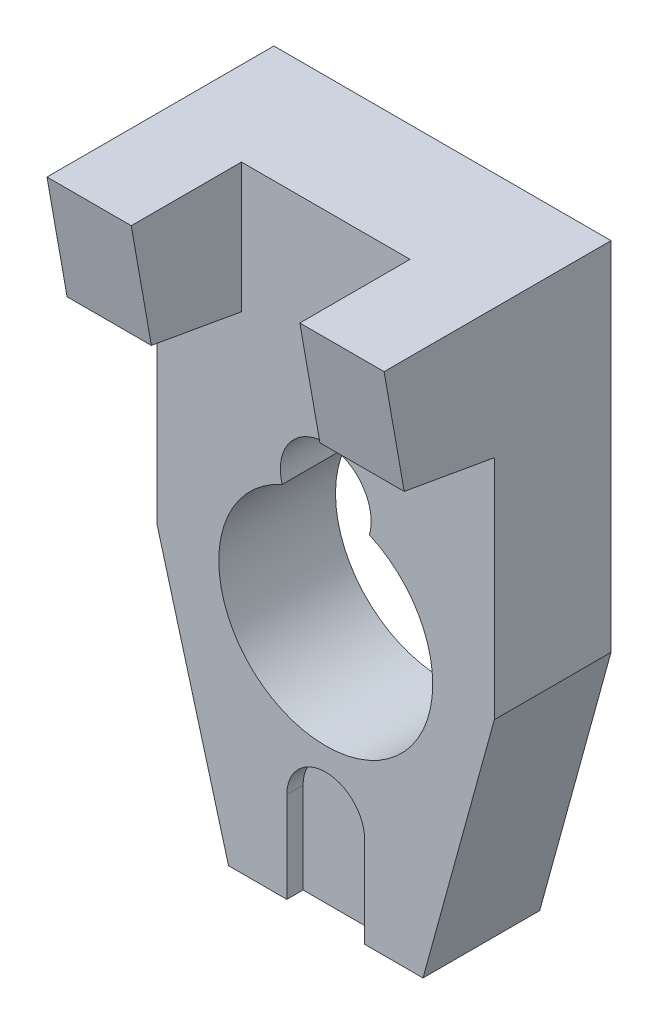
SolidWorks part; units mm, degrees
ref_plane "前视基准面" through (0, 0, 0) normal (0, 0, 1) x (1, 0, 0)
ref_plane "上视基准面" through (0, 0, 0) normal (0, 1, 0) x (1, 0, 0)
ref_plane "右视基准面" through (0, 0, 0) normal (1, 0, 0) x (0, 0, -1)
other "Configuration Table"
sketch "草图1" plane through (0, 0, 0) normal (0, 0, 1) x (1, 0, 0)
  line L0 (-26, 0) -> (-15, -40)
  line L1 (-26, 55) -> (26, 55)
  line L2 (-26, 55) -> (-26, 0)
  line L4 (26, 55) -> (26, 0)
  line L5 (-26, 55) -> (16.4377, -34.772) construction
  line L6 (-16.4377, -34.772) -> (26, 55) construction
  line L7 (-15, -40) -> (15, -40)
  line L8 (15, -40) -> (26, 0)
  arc A0 (-6.7276, 15.0662) -> (6.7276, 15.0662) centre (0, 0) ccw
  arc A1 (6.7276, 15.0662) -> (-6.7276, 15.0662) centre (0, 17) ccw
  point P0 (0, 0)
  point P7 (-27.4814, -8.5782)
  point P9 (24.5453, -7.5509)
  point P14 (0, -40)
  point P15 (0, 0)
  point P18 (0, 0)
  dimension "D2" = 33
  dimension "D3" = 14
  dimension "D4" = 17
  dimension "D1" = 52
  dimension "D5" = 30
  dimension "D6" = 40
  dimension "D7" = 95
  dimension "D8" = 26
extrude "凸台-拉伸1" add sketch "草图1" along normal blind 18
sketch "草图2" plane through (26, 0, 0) normal (1, 0, 0) x (0, 0, -1)
  line L0 (-18, 55) -> (-18, 35)
  line L1 (-18, 0) -> (-18, 55) construction
  line L2 (-18, 35) -> (-31.9058, 37.452)
  line L3 (-31.9058, 37.452) -> (-35, 55)
  line L4 (-35, 55) -> (-18, 55)
  line L5 (0, 0) -> (0, 55) construction
  dimension "D1" = 20
  dimension "D2" = 10
  dimension "D3" = 10
  dimension "D4" = 35
extrude "凸台-拉伸2" add sketch "草图2" against normal blind 13
mirror "镜向1" about plane through (0, 0, 0) normal (1, 0, 0) of "凸台-拉伸2"
sketch "草图3" plane through (0, 0, 18) normal (0, 0, 1) x (1, 0, 0)
  line L0 (-15, -40) -> (15, -40) construction
  line L2 (-6, -26) -> (-6, -55.4816)
  line L3 (-6, -55.4816) -> (6, -55.4816)
  line L4 (6, -26) -> (6, -55.4816)
  arc A0 (6, -26) -> (-6, -26) centre (0, -26) ccw
  dimension "D1" = 12
  dimension "D2" = 14
extrude "切除-拉伸1" cut sketch "草图3" against normal mid plane 5
